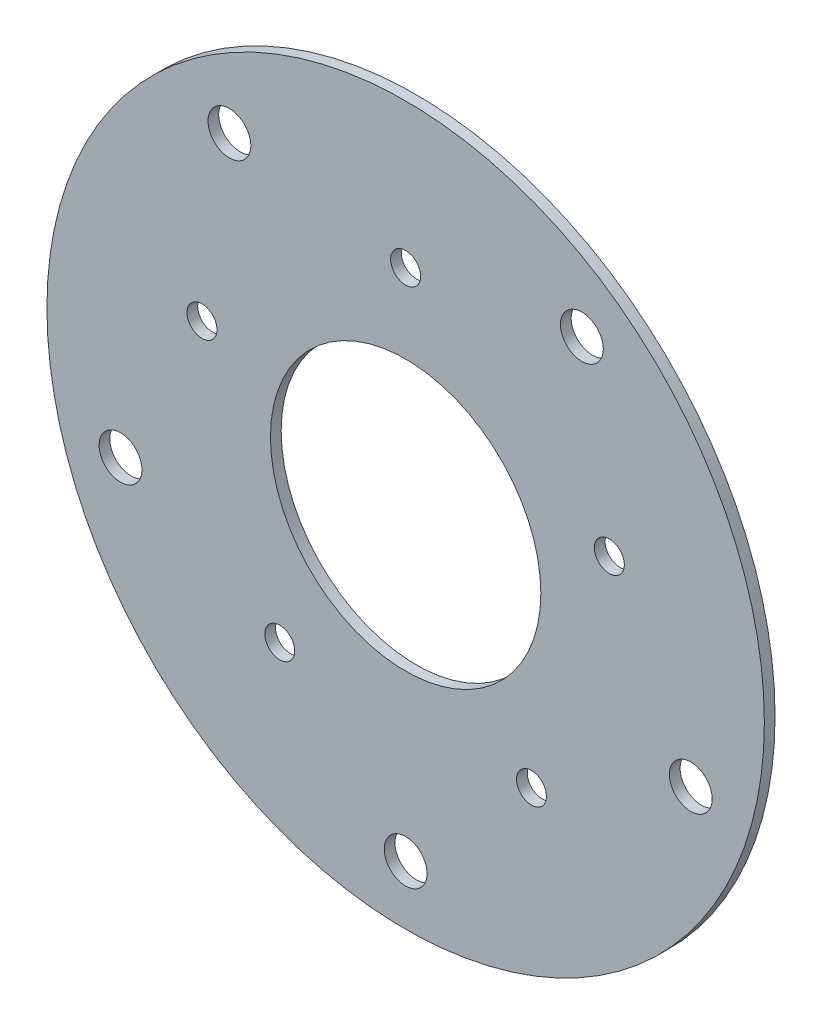
SolidWorks part; units mm, degrees
ref_plane "前视基准面" through (0, 0, 0) normal (0, 0, 1) x (1, 0, 0)
ref_plane "上视基准面" through (0, 0, 0) normal (0, 1, 0) x (1, 0, 0)
ref_plane "右视基准面" through (0, 0, 0) normal (1, 0, 0) x (0, 0, -1)
sketch "草图1" plane through (0, 0, 0) normal (0, 0, 1) x (1, 0, 0)
  line L0 (-26.6296, -8.6525) -> (0, -28) construction
  line L1 (-13.3148, -18.3262) -> (-4.9931, -6.8724) construction
  circle A0 centre (0, 0) radius 33.5
  circle A1 centre (0, 0) radius 12.625
  circle A2 centre (0, -28) radius 2
  circle A3 centre (-26.6296, -8.6525) radius 2
  circle A4 centre (-16.458, 22.6525) radius 2
  circle A5 centre (16.458, 22.6525) radius 2
  circle A6 centre (26.6296, -8.6525) radius 2
  circle A7 centre (0, 0) radius 20 construction
  circle A8 centre (-11.7557, -16.1803) radius 1.4
  circle A9 centre (-19.0211, 6.1803) radius 1.4
  circle A10 centre (0, 20) radius 1.4
  circle A11 centre (19.0211, 6.1803) radius 1.4
  circle A12 centre (11.7557, -16.1803) radius 1.4
  dimension "D1" = 67
  dimension "D2" = 40
  dimension "D3" = 2.8
  dimension "D4" = 25.25
extrude "凸台-拉伸1" add sketch "草图1" along normal blind 1 contours A0
